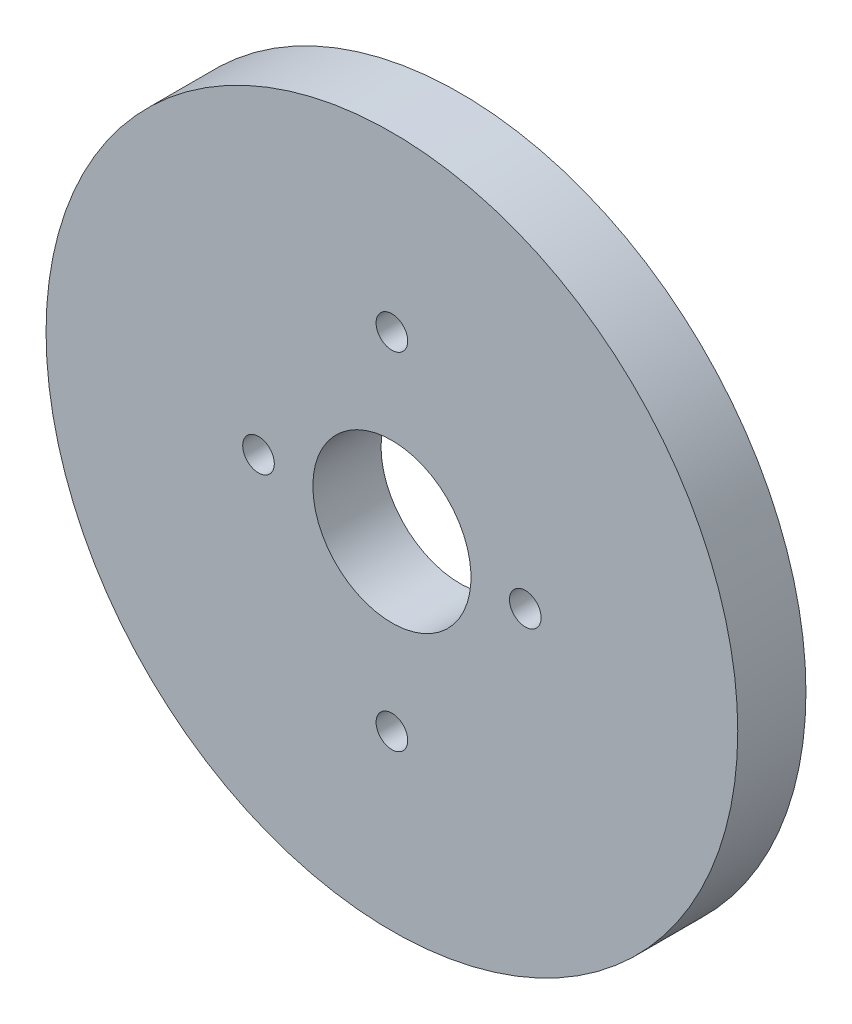
SolidWorks part; units mm, degrees
material "AISI 1020"
ref_plane "Front Plane" through (0, 0, 0) normal (0, 0, 1) x (1, 0, 0)
ref_plane "Top Plane" through (0, 0, 0) normal (0, 1, 0) x (1, 0, 0)
ref_plane "Right Plane" through (0, 0, 0) normal (1, 0, 0) x (0, 0, -1)
sketch "Sketch1" plane through (0, 0, 0) normal (0, 0, 1) x (1, 0, 0)
  line L0 (0, 0) -> (6.75, 0) construction
  line L1 (0, 0) -> (0, 8.75) construction
  circle A0 centre (0, 0) radius 17.5
  circle A1 centre (0, 0) radius 4
  circle A2 centre (6.75, 0) radius 0.8
  circle A3 centre (0, 8.75) radius 0.8
  circle A4 centre (0, -8.75) radius 0.8
  circle A5 centre (-6.75, 0) radius 0.8
  dimension "D1" = 8
  dimension "D2" = 35
  dimension "D3" = 1.6
  dimension "D4" = 6.75
  dimension "D5" = 8.75
extrude "Boss-Extrude1" add sketch "Sketch1" along normal blind 3.45
